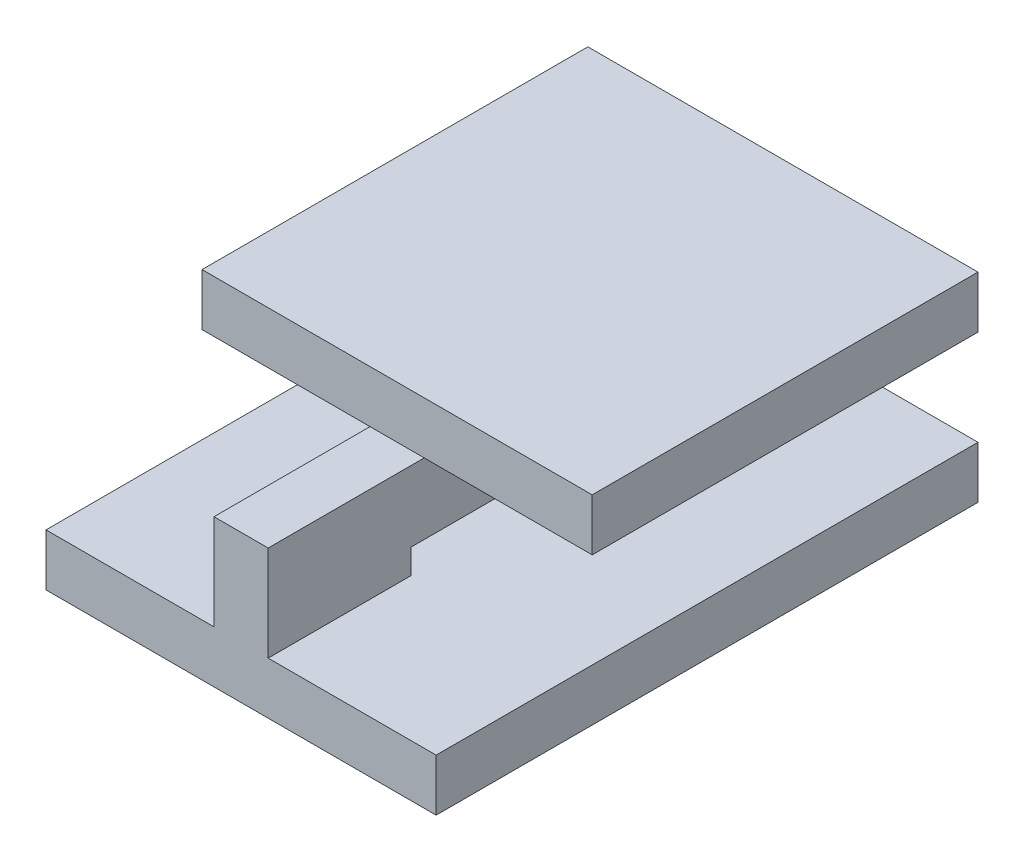
SolidWorks part; units mm, degrees
ref_plane "Front Plane" through (0, 0, 0) normal (0, 0, 1) x (1, 0, 0)
ref_plane "Top Plane" through (0, 0, 0) normal (0, 1, 0) x (1, 0, 0)
ref_plane "Right Plane" through (0, 0, 0) normal (1, 0, 0) x (0, 0, -1)
sketch "Sketch1" plane through (0, 0, 0) normal (0, 1, 0) x (1, 0, 0)
  line L1 (0, 0) -> (90, 0)
  line L2 (0, 0) -> (0, 125)
  line L3 (0, 125) -> (90, 125)
  line L4 (90, 0) -> (90, 125)
  dimension "D1" = 90
  dimension "D2" = 125
extrude "Boss-Extrude1" add sketch "Sketch1" along normal blind 12
sketch "Sketch2" plane through (0, 12, 0) normal (0, 1, 0) x (1, 0, 0)
  line L0 (0, 0) -> (90, 0) construction
  line L1 (38.75, 0) -> (51.25, 0)
  line L2 (38.75, 0) -> (38.75, 125)
  line L3 (38.75, 125) -> (51.25, 125)
  line L4 (51.25, 0) -> (51.25, 125)
  line L5 (90, 125) -> (0, 125) construction
  point P8 (45, 0)
  point P9 (45, 0)
  dimension "D1" = 12.5
extrude "Boss-Extrude2" add sketch "Sketch2" along normal blind 22
sketch "Sketch3" plane through (0, 34, 0) normal (0, 1, 0) x (1, 0, 0)
  line L1 (0, 125) -> (90, 125)
  line L2 (0, 125) -> (0, 36)
  line L3 (0, 36) -> (90, 36)
  line L4 (90, 125) -> (90, 36)
  line L5 (38.75, 125) -> (0, 125) construction
  line L6 (45, 125) -> (45, 0)
  line L8 (51.25, 125) -> (38.75, 125) construction
  line L9 (38.75, 0) -> (51.25, 0) construction
  point P12 (0, 0)
  point P15 (45, 125)
  line M7 (38.75, 125) -> (38.75, 0)
  line M9 (51.25, 0) -> (51.25, 125)
  line M10 (51.25, 125) -> (38.75, 125)
  dimension "D1" = 89
  dimension "D2" = 90
extrude "Boss-Extrude3" add sketch "Sketch3" along normal blind 12 contours L4 L1 L3 M9 | L2 L3 L1 M7 | L6 L1 L3 M7 | L6 L3 M10 M9
sketch "Sketch4" plane through (51.25, 0, 0) normal (1, 0, 0) x (0, 0, -1)
  line L1 (125, 12) -> (32.9566, 12)
  line L2 (125, 12) -> (125, 17.6974)
  line L3 (125, 17.6974) -> (32.9566, 17.6974)
  line L4 (32.9566, 12) -> (32.9566, 17.6974)
extrude "Cut-Extrude1" cut sketch "Sketch4" against normal through all
